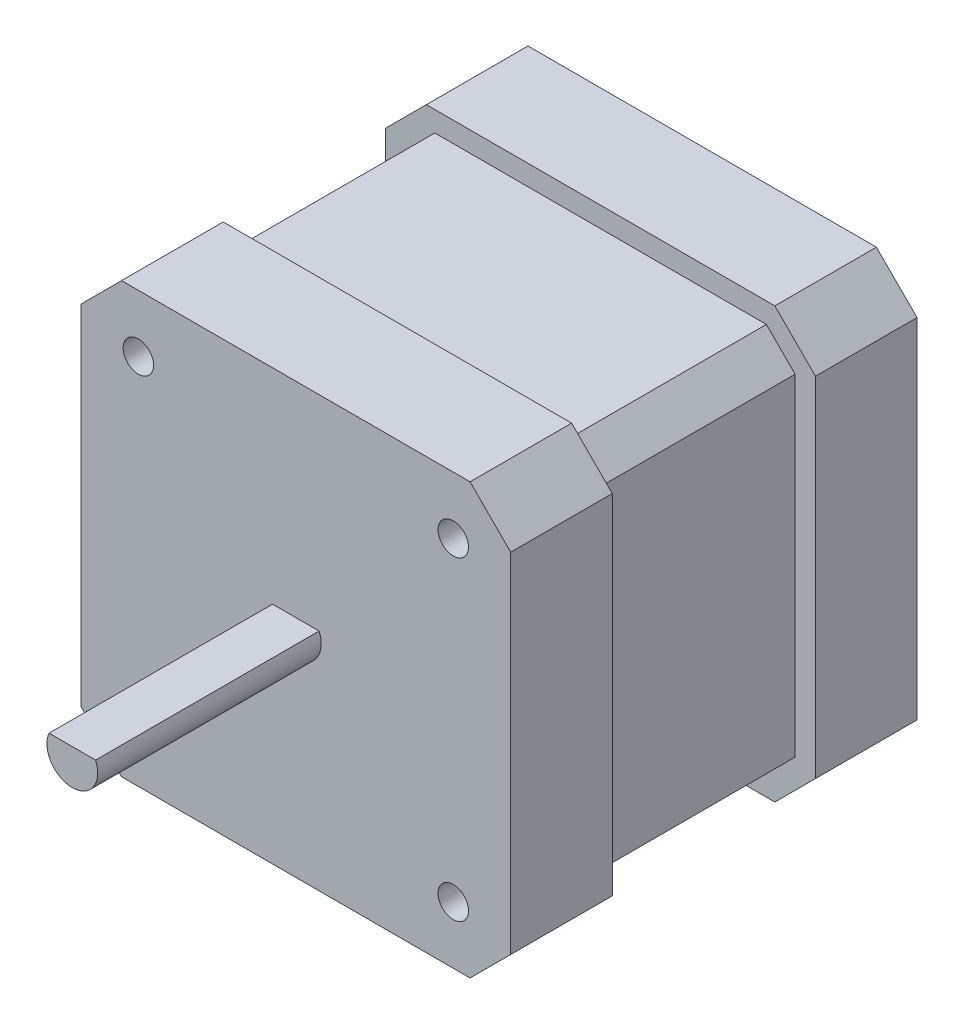
SolidWorks part; units mm, degrees
ref_plane "Front Plane" through (0, 0, 0) normal (0, 0, 1) x (1, 0, 0)
ref_plane "Top Plane" through (0, 0, 0) normal (0, 1, 0) x (1, 0, 0)
ref_plane "Right Plane" through (0, 0, 0) normal (1, 0, 0) x (0, 0, -1)
sketch "Sketch1" plane through (0, 0, 0) normal (0, 0, 1) x (1, 0, 0)
  line L0 (-21.15, 17.15) -> (-17.15, 21.15)
  line L1 (-17.15, -21.15) -> (17.15, -21.15)
  line L2 (-21.15, -17.15) -> (-21.15, 17.15)
  line L3 (-17.15, 21.15) -> (17.15, 21.15)
  line L4 (21.15, -17.15) -> (21.15, 17.15)
  line L5 (-21.15, -21.15) -> (21.15, 21.15) construction
  line L6 (-21.15, 21.15) -> (21.15, -21.15) construction
  line L7 (17.15, 21.15) -> (21.15, 17.15)
  line L8 (17.15, -21.15) -> (21.15, -17.15)
  line L9 (-21.15, -17.15) -> (-17.15, -21.15)
  point P0 (0, 0)
  dimension "D1" = 42.3
  dimension "D2" = 42.3
extrude "Boss-Extrude1" add sketch "Sketch1" along normal blind 10 contours L3 L7 L4 L8 L1 L9 L2 L0
sketch "Sketch2" plane through (0, 0, 0) normal (0, 0, -1) x (-1, 0, 0)
  line L16 (19.15, 16.3216) -> (16.3216, 19.15)
  line L17 (16.3216, 19.15) -> (-16.3216, 19.15)
  line L18 (-16.3216, 19.15) -> (-19.15, 16.3216)
  line L19 (-19.15, 16.3216) -> (-19.15, -16.3216)
  line L20 (-19.15, -16.3216) -> (-16.3216, -19.15)
  line L21 (-16.3216, -19.15) -> (16.3216, -19.15)
  line L22 (16.3216, -19.15) -> (19.15, -16.3216)
  line L23 (19.15, -16.3216) -> (19.15, 16.3216)
  line L24 (19.15, 16.3216) -> (16.3216, 19.15)
  line L25 (16.3216, 19.15) -> (-16.3216, 19.15)
  line L26 (-16.3216, 19.15) -> (-19.15, 16.3216)
  line L27 (-19.15, 16.3216) -> (-19.15, -16.3216)
  line L28 (-19.15, -16.3216) -> (-16.3216, -19.15)
  line L29 (-16.3216, -19.15) -> (16.3216, -19.15)
  line L30 (16.3216, -19.15) -> (19.15, -16.3216)
  line L31 (19.15, -16.3216) -> (19.15, 16.3216)
  dimension "D1" = 2
extrude "Boss-Extrude2" add sketch "Sketch2" along normal blind 20
sketch "Sketch3" plane through (0, 0, -20) normal (0, 0, -1) x (-1, 0, 0)
  line L8 (21.15, 17.15) -> (17.15, 21.15)
  line L9 (17.15, 21.15) -> (-17.15, 21.15)
  line L10 (-17.15, 21.15) -> (-21.15, 17.15)
  line L11 (-21.15, 17.15) -> (-21.15, -17.15)
  line L12 (-21.15, -17.15) -> (-17.15, -21.15)
  line L13 (-17.15, -21.15) -> (17.15, -21.15)
  line L14 (17.15, -21.15) -> (21.15, -17.15)
  line L15 (21.15, -17.15) -> (21.15, 17.15)
  line L16 (21.15, 17.15) -> (17.15, 21.15)
  line L17 (17.15, 21.15) -> (-17.15, 21.15)
  line L18 (-17.15, 21.15) -> (-21.15, 17.15)
  line L19 (-21.15, 17.15) -> (-21.15, -17.15)
  line L20 (-21.15, -17.15) -> (-17.15, -21.15)
  line L21 (-17.15, -21.15) -> (17.15, -21.15)
  line L22 (17.15, -21.15) -> (21.15, -17.15)
  line L23 (21.15, -17.15) -> (21.15, 17.15)
  dimension "D1" = 0
extrude "Boss-Extrude3" add sketch "Sketch3" along normal blind 10
sketch "Sketch4" plane through (0, 0, 10) normal (0, 0, 1) x (1, 0, 0)
  line L0 (-2.2913, 1) -> (2.2913, 1)
  circle A0 centre (0, 0) radius 2.5
  dimension "D1" = 5
  dimension "D2" = 1
extrude "Boss-Extrude4" add sketch "Sketch4" along normal blind 22 contours L0 A0
sketch "Sketch6" plane through (0, 0, 10) normal (0, 0, 1) x (1, 0, 0)
  line L1 (-15.5, -15.5) -> (15.5, -15.5) construction
  line L2 (-15.5, -15.5) -> (-15.5, 15.5) construction
  line L3 (-15.5, 15.5) -> (15.5, 15.5) construction
  line L4 (15.5, -15.5) -> (15.5, 15.5) construction
  line L5 (-15.5, -15.5) -> (15.5, 15.5) construction
  line L6 (-15.5, 15.5) -> (15.5, -15.5) construction
  circle A0 centre (-15.5, 15.5) radius 1.5
  circle A1 centre (15.5, 15.5) radius 1.5
  circle A2 centre (15.5, -15.5) radius 1.5
  circle A3 centre (-15.5, -15.5) radius 1.5
  point P0 (0, 0)
  dimension "D3" = 3
  dimension "D1" = 31
  dimension "D2" = 31
extrude "Cut-Extrude1" cut sketch "Sketch6" against normal blind 4.5
